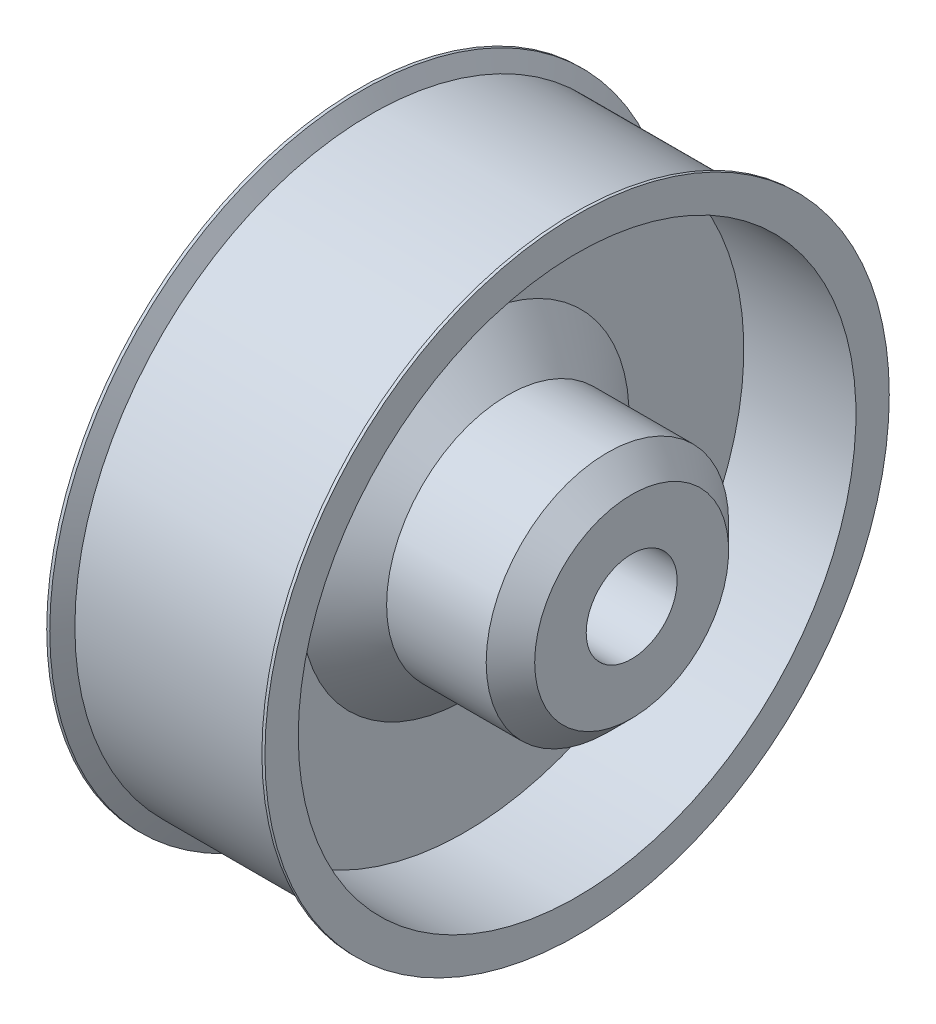
SolidWorks part; units mm, degrees
ref_plane "Front Plane" through (0, 0, 0) normal (0, 0, 1) x (1, 0, 0)
ref_plane "Top Plane" through (0, 0, 0) normal (0, 1, 0) x (1, 0, 0)
ref_plane "Right Plane" through (0, 0, 0) normal (1, 0, 0) x (0, 0, -1)
sketch "Sketch1" plane through (0, 0, 0) normal (0, 0, 1) x (1, 0, 0)
  line L0 (-27.1184, 0) -> (0, 0) construction
  line L1 (0, 0) -> (0, 27.0711) construction
  line L2 (-7.5, 6) -> (-17.5063, 3.75)
  line L3 (-17.5063, 3.75) -> (-18, 0)
  line L4 (-18, 0) -> (0, 0)
  line L5 (0, 0) -> (0, 7.5)
  line L6 (0, 7.5) -> (27.5, 7.5)
  line L7 (27.5, 7.5) -> (27.5, 16)
  line L8 (27.5, 16) -> (23.5, 20)
  line L9 (23.5, 20) -> (7.0711, 20)
  line L10 (7.0711, 20) -> (0, 27.0711)
  line L11 (-7.5, 6) -> (-7.5, 12.9377)
  line L12 (-7.5, 33.0623) -> (-7.5, 43)
  line L13 (0, 27.0711) -> (0, 46)
  line L14 (0, 46) -> (18.5, 46)
  line L15 (18.5, 46) -> (18.5, 51.5)
  line L16 (18.5, 51.5) -> (18, 51.5)
  line L17 (18, 51.5) -> (16.5, 48.8543)
  line L18 (16.5, 48.8543) -> (-15.5, 48.8543)
  line L19 (-15.5, 48.8543) -> (-17, 51.5)
  line L20 (-17, 51.5) -> (-17.5, 51.5)
  line L21 (-17.5, 51.5) -> (-17.5, 48)
  line L22 (-15.5, 46) -> (-10.5, 46)
  arc A0 (-9.6429, 15.8126) -> (-9.6429, 30.1874) centre (-7.5, 23) cw
  arc A1 (-7.5, 12.9377) -> (-9.6429, 15.8126) centre (-10.5, 12.9377) ccw
  arc A2 (-9.6429, 30.1874) -> (-7.5, 33.0623) centre (-10.5, 33.0623) ccw
  arc A3 (-7.5, 43) -> (-10.5, 46) centre (-10.5, 43) ccw
  arc A4 (-17.5, 48) -> (-15.5, 46) centre (-15.5, 48) ccw
  point P31 (-7.5, 46)
  point P34 (-17.5, 46)
  dimension "D7" = 7.5
  dimension "D23" = 3
  dimension "D24" = 2
  dimension "D1" = 18
  dimension "D2" = 82.5
  dimension "D3" = 7.5
  dimension "D4" = 3.75
  dimension "D5" = 6
  dimension "D6" = 23
  dimension "D8" = 7.5
  dimension "D9" = 45.5
  dimension "D10" = 20
  dimension "D11" = 4
  dimension "D12" = 45
  dimension "D13" = 10
  dimension "D14" = 45
  dimension "D15" = 36
  dimension "D16" = 10
  dimension "D17" = 46
  dimension "D18" = 51.5
  dimension "D19" = 0.5
  dimension "D20" = 0.5
  dimension "D21" = 32
  dimension "D22" = 2
revolve "Revolve1" add sketch "Sketch1" angle 360 about L4
sketch "Sketch2" plane through (-7.5, 0, 0) normal (-1, 0, 0) x (0, 0, 1)
  line L0 (0, 0) -> (0, 54.7729) construction
  line L2 (-2.8868, 37.5) -> (-1.4434, 35)
  line L3 (-1.4434, 35) -> (1.4434, 35)
  line L4 (1.4434, 35) -> (2.8868, 37.5)
  line L5 (2.8868, 37.5) -> (1.4434, 40)
  line L6 (1.4434, 40) -> (-1.4434, 40)
  line L7 (-1.4434, 40) -> (-2.8868, 37.5)
  circle A0 centre (0, 37.5) radius 2.5 construction
  dimension "D1" = 5
  dimension "D2" = 37.5
extrude "Boss-Extrude1" add sketch "Sketch2" along normal blind 3
pattern_circular "CirPattern1" count 6 over 360 about axis through (0, 0, 0) along (1, 0, 0) of "Boss-Extrude1"
sketch "Sketch3" plane through (-7.5, 0, 0) normal (-1, 0, 0) x (0, 0, 1)
  line L1 (-1.4434, 12.5) -> (-2.8868, 10)
  line L2 (-2.8868, 10) -> (-1.4434, 7.5)
  line L3 (-1.4434, 7.5) -> (1.4434, 7.5)
  line L4 (1.4434, 7.5) -> (2.8868, 10)
  line L5 (2.8868, 10) -> (1.4434, 12.5)
  line L6 (1.4434, 12.5) -> (-1.4434, 12.5)
  circle A0 centre (0, 10) radius 2.5 construction
  dimension "D1" = 5
  dimension "D2" = 10
extrude "Boss-Extrude2" add sketch "Sketch3" along normal blind 3
pattern_circular "CirPattern3" count 5 over 360 about axis through (0, 0, 0) along (1, 0, 0) of "Boss-Extrude2"
